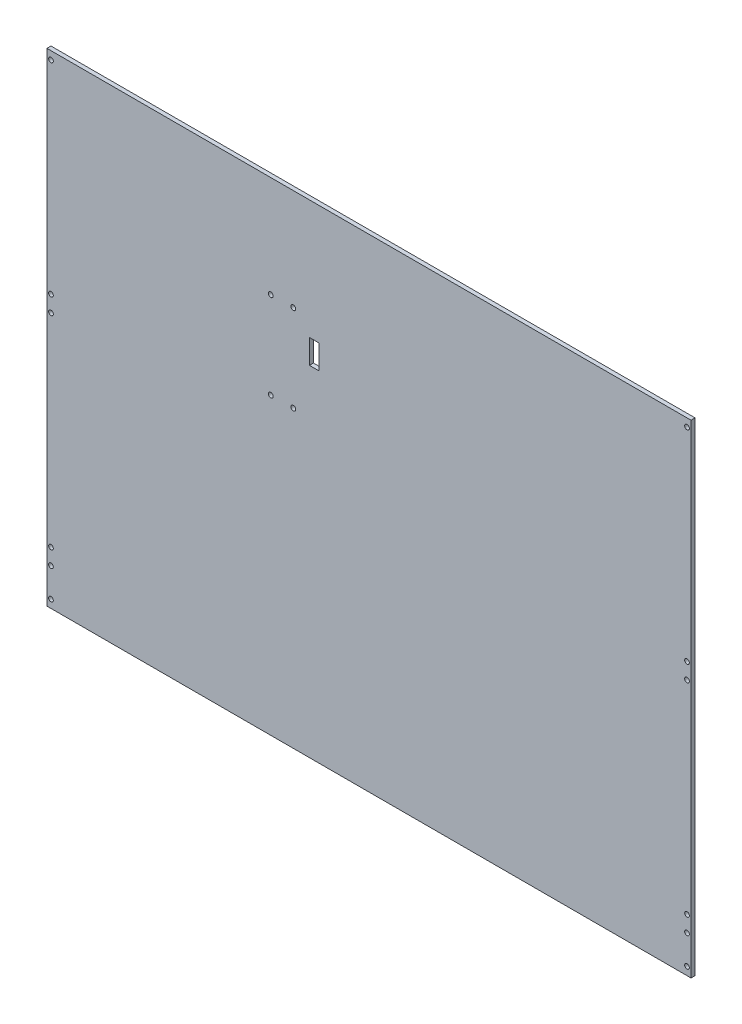
SolidWorks part; units mm, degrees
ref_plane "Front Plane" through (0, 0, 0) normal (0, 0, 1) x (1, 0, 0)
ref_plane "Top Plane" through (0, 0, 0) normal (0, 1, 0) x (1, 0, 0)
ref_plane "Right Plane" through (0, 0, 0) normal (1, 0, 0) x (0, 0, -1)
sketch "Sketch1" plane through (0, 0, 0) normal (0, 0, 1) x (1, 0, 0)
  line L1 (-254, -190.5) -> (254, -190.5)
  line L2 (-254, -190.5) -> (-254, 190.5)
  line L3 (-254, 190.5) -> (254, 190.5)
  line L4 (254, -190.5) -> (254, 190.5)
  line L5 (-254, -190.5) -> (254, 190.5) construction
  line L6 (-254, 190.5) -> (254, -190.5) construction
  point P0 (0, 0)
  dimension "D1" = 508
  dimension "D2" = 381
extrude "Boss-Extrude1" add sketch "Sketch1" along normal blind 3.175
sketch "Sketch3" plane through (0, 0, 3.175) normal (0, 0, 1) x (1, 0, 0)
  line L0 (-254, 190.5) -> (-254, -190.5) construction
  line L1 (-46.99, 77.47) -> (-39.37, 77.47)
  line L2 (-46.99, 77.47) -> (-46.99, 96.52)
  line L3 (-46.99, 96.52) -> (-39.37, 96.52)
  line L4 (-39.37, 77.47) -> (-39.37, 96.52)
  line L5 (254, 190.5) -> (-254, 190.5) construction
  dimension "D1" = 207.01
  dimension "D2" = 7.62
  dimension "D3" = 113.03
  dimension "D4" = 19.05
extrude "Cut-Extrude2" cut sketch "Sketch3" against normal up to surface (3.175 mm away) up to face at (0, 0, 0)
sketch "Sketch2" plane through (0, 0, 3.175) normal (0, 0, 1) x (1, 0, 0)
  line L0 (-250.825, 190.5) -> (-250.825, -190.5) construction
  line L1 (254, 190.5) -> (-254, 190.5) construction
  line L2 (-254, -190.5) -> (254, -190.5) construction
  line L3 (250.825, 190.5) -> (250.825, -190.5) construction
  line L4 (254, -190.5) -> (254, 190.5) construction
  line L5 (-254, 190.5) -> (-254, -190.5) construction
  line L6 (0, 0) -> (0, -50000) construction
  line L8 (-39.37, 96.52) -> (-46.99, 96.52) construction
  circle A0 centre (-250.825, -184.15) radius 1.8542
  circle A1 centre (-250.825, 184.15) radius 1.8542
  circle A2 centre (250.825, 184.15) radius 1.8542
  circle A3 centre (250.825, -184.15) radius 1.8542
  circle A4 centre (-250.825, 24.13) radius 1.8542
  circle A5 centre (250.825, 24.13) radius 1.8542
  circle A6 centre (-250.825, 11.43) radius 1.8542
  circle A7 centre (-250.825, -148.59) radius 1.8542
  circle A8 centre (-250.825, -161.29) radius 1.8542
  circle A9 centre (250.825, -161.29) radius 1.8542
  circle A10 centre (250.825, -148.59) radius 1.8542
  circle A11 centre (250.825, 11.43) radius 1.8542
  circle A12 centre (-77.4887, 110.49) radius 1.905
  circle A13 centre (-77.4887, 41.91) radius 1.905
  circle A14 centre (-59.7087, 110.49) radius 1.905
  circle A15 centre (-59.7087, 41.91) radius 1.905
  point P33 (0, -190.5)
  dimension "D3" = 3.7084
  dimension "D10" = 12.7
  dimension "D14" = 3.81
  dimension "D12" = 17.78
  dimension "D1" = 3.175
  dimension "D2" = 3.175
  dimension "D4" = 6.35
  dimension "D5" = 6.35
  dimension "D6" = 6.35
  dimension "D7" = 6.35
  dimension "D8" = 160.02
  dimension "D9" = 160.02
  dimension "D11" = 29.21
  dimension "D13" = 68.58
  dimension "D15" = 12.7187
  dimension "D16" = 13.97
extrude "Cut-Extrude1" cut sketch "Sketch2" against normal blind 3.175
